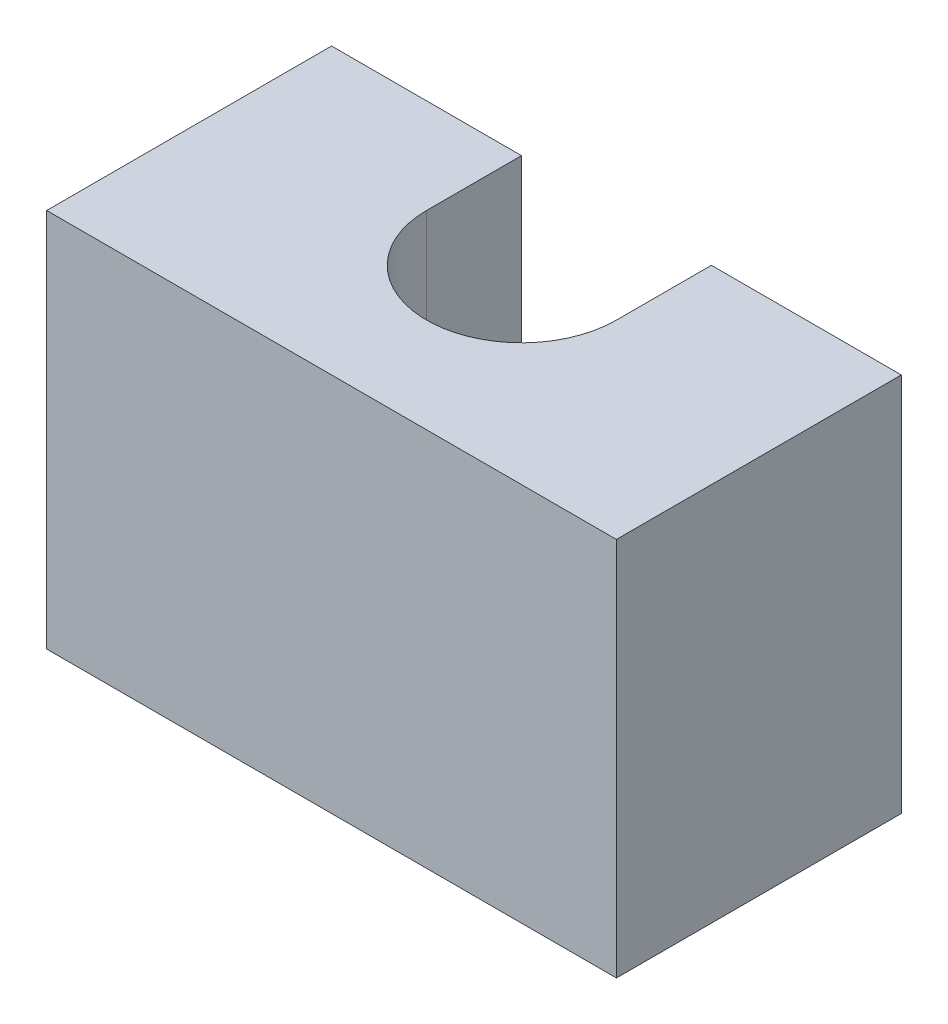
SolidWorks part; units mm, degrees
ref_plane "Přední rovina" through (0, 0, 0) normal (0, 0, 1) x (1, 0, 0)
ref_plane "Horní rovina" through (0, 0, 0) normal (0, 1, 0) x (1, 0, 0)
ref_plane "Pravá rovina" through (0, 0, 0) normal (1, 0, 0) x (0, 0, -1)
sketch "Sketch2" plane through (0, 0, 0) normal (0, 1, 0) x (1, 0, 0)
  line L0 (-5, 0) -> (-5, -5)
  line L3 (15, -15) -> (-15, -15)
  line L4 (-15, -15) -> (-15, 0)
  line L5 (-15, 0) -> (-5, 0)
  line L6 (0, 0) -> (0, -15) construction
  line L7 (15, 0) -> (5, 0)
  line L8 (15, -15) -> (15, 0)
  line L9 (5, 0) -> (5, -5)
  arc A0 (-5, -5) -> (5, -5) centre (0, -5) ccw
  point P4 (-30, -31.1559)
  dimension "D2" = 5
  dimension "D1" = 10
  dimension "D3" = 15
  dimension "D4" = 5
extrude "Boss-Extrude1" add sketch "Sketch2" along normal blind 20
equation "\"R\"= 5"
equation "\"D2@Sketch2\"=\"R\""
equation "\"D1@Sketch2\"=\"R\" *2"
equation "\"D3@Sketch2\"=\"R\"*3"
equation "\"D4@Sketch2\"=\"R\""
